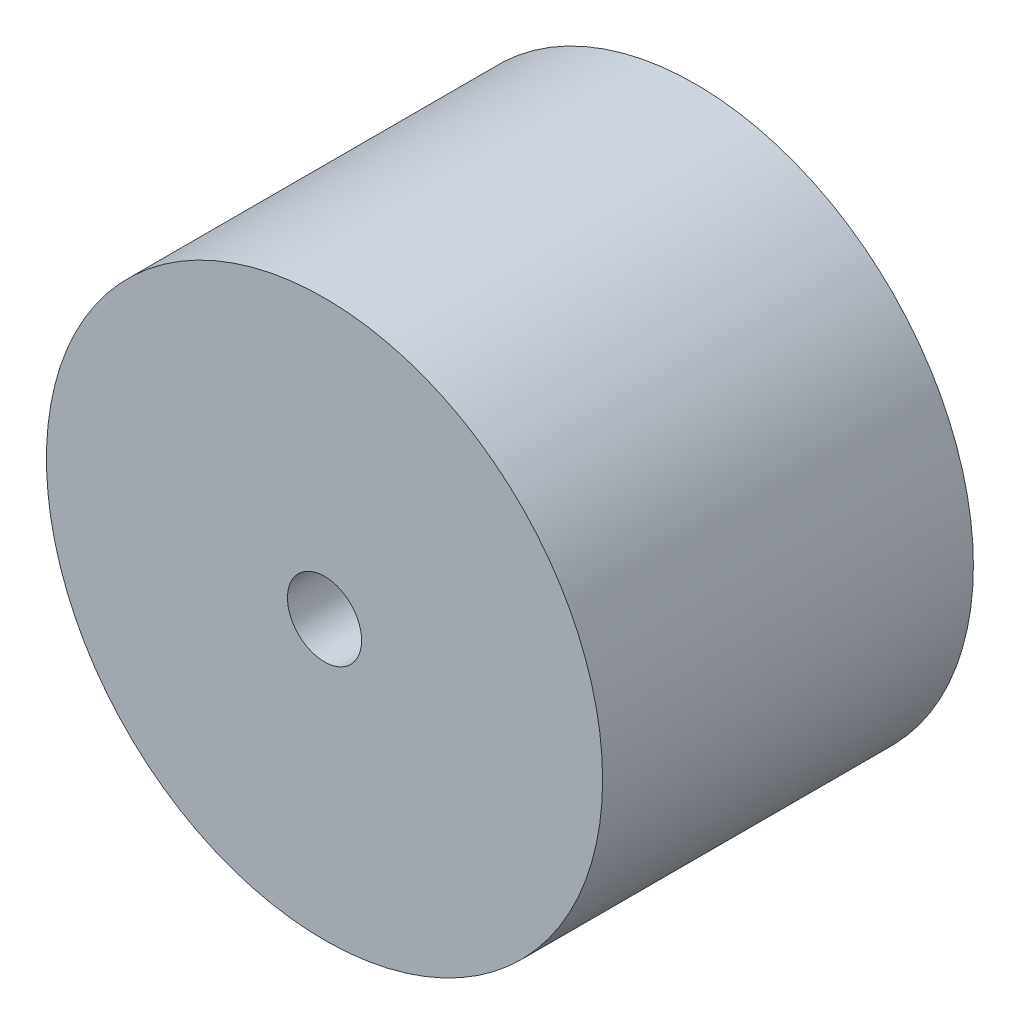
SolidWorks part; units mm, degrees
ref_plane "Front Plane" through (0, 0, 0) normal (0, 0, 1) x (1, 0, 0)
ref_plane "Top Plane" through (0, 0, 0) normal (0, 1, 0) x (1, 0, 0)
ref_plane "Right Plane" through (0, 0, 0) normal (1, 0, 0) x (0, 0, -1)
sketch "Sketch1" plane through (0, 0, 0) normal (0, 0, 1) x (1, 0, 0)
  circle A0 centre (0, 0) radius 30
  circle A1 centre (0, 0) radius 4
  dimension "D1" = 60
  dimension "D2" = 8
extrude "Boss-Extrude1" add sketch "Sketch1" along normal blind 40
